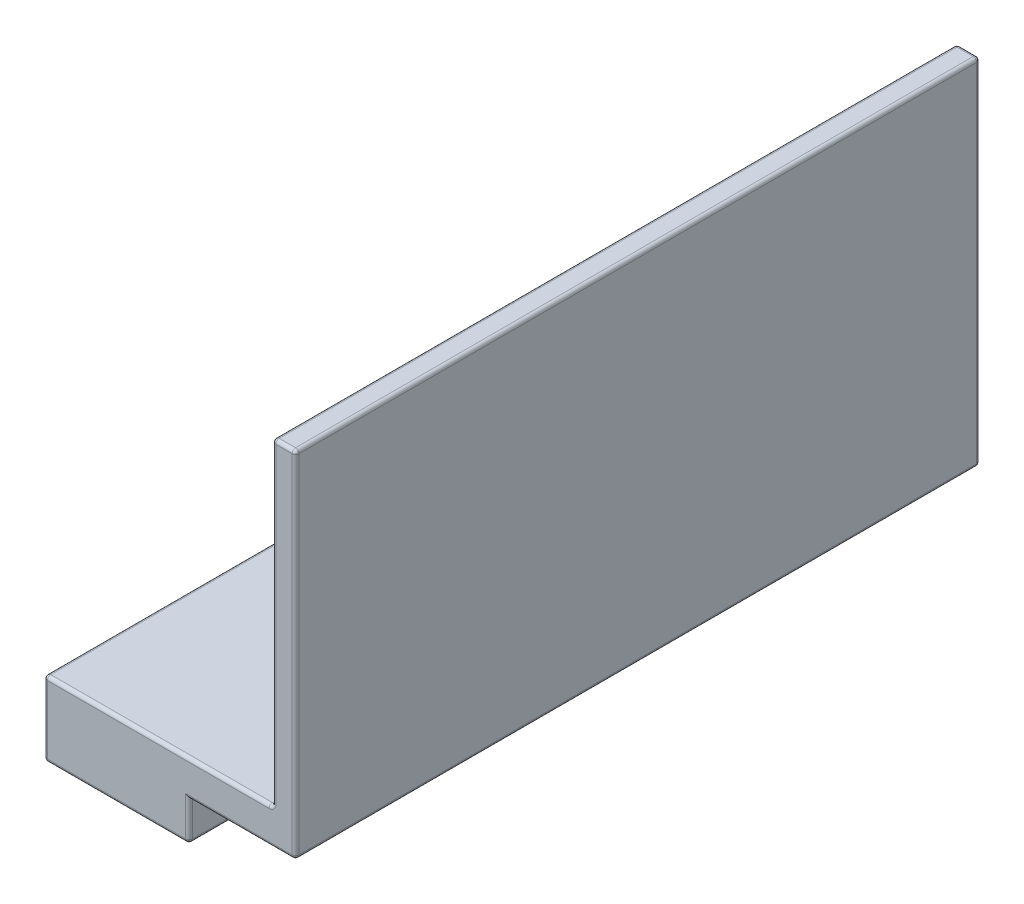
SolidWorks part; units mm, degrees
ref_plane "Front Plane" through (0, 0, 0) normal (0, 0, 1) x (1, 0, 0)
ref_plane "Top Plane" through (0, 0, 0) normal (0, 1, 0) x (1, 0, 0)
ref_plane "Right Plane" through (0, 0, 0) normal (1, 0, 0) x (0, 0, -1)
sketch "Sketch1" plane through (0, 0, 0) normal (0, 0, 1) x (1, 0, 0)
  line L1 (0, 0) -> (735, 0)
  line L2 (735, 0) -> (735, 1150.4)
  line L3 (735, 1150.4) -> (667.5, 1150.4)
  line L4 (667.5, 1150.4) -> (667.5, 218.8)
  line L5 (667.5, 218.8) -> (0, 218.8)
  line L8 (0, 218.8) -> (0, 0)
  dimension "D1" = 667.5
  dimension "D3" = 67.5
  dimension "D4" = 1150.4
  dimension "D5" = 218.8
extrude "Boss-Extrude1" add sketch "Sketch1" along normal blind 2000
sketch "Sketch3" plane through (0, 0, 0) normal (0, 0, -1) x (-1, 0, 0)
  line L1 (-735, 0) -> (-424, 0)
  line L2 (-735, 0) -> (-735, 115)
  line L3 (-735, 115) -> (-424, 115)
  line L4 (-424, 0) -> (-424, 115)
  dimension "D1" = 311
  dimension "D2" = 115
extrude "Cut-Extrude1" cut sketch "Sketch3" against normal up to next
sketch "Sketch2" plane through (0, 0, 0) normal (-1, 0, 0) x (0, 0, 1)
  line L0 (2000, 0) -> (0, 0) construction
  line L1 (20, 198.8) -> (1980, 198.8)
  line L2 (20, 198.8) -> (20, 20)
  line L3 (20, 20) -> (1980, 20)
  line L4 (1980, 198.8) -> (1980, 20)
  line L5 (20, 198.8) -> (1980, 20) construction
  line L6 (20, 20) -> (1980, 198.8) construction
  line L7 (0, 218.8) -> (0, 0) construction
  line L8 (2000, 218.8) -> (2000, 0) construction
  line L9 (2000, 218.8) -> (0, 218.8) construction
  point P0 (1000, 109.4)
  dimension "D1" = 20
  dimension "D2" = 20
  dimension "D3" = 20
  dimension "D4" = 20
extrude "Cut-Extrude2" cut sketch "Sketch2" against normal blind 310
fillet "Fillet2" radius 10 23 edges at (667.5, 684.6, 2000) (212, 0, 2000) (579.5, 115, 2000) (424, 57.5, 2000) (424, 0, 1000) (212, 0, 0) (424, 57.5, 0) (735, 115, 1000) (579.5, 115, 0) (735, 632.7, 0) (735, 632.7, 2000) (735, 1150.4, 1000) (701.25, 1150.4, 0) (701.25, 1150.4, 2000) (667.5, 1150.4, 1000) (333.75, 218.8, 2000) (667.5, 218.8, 1000) (667.5, 684.6, 0) (333.75, 218.8, 0) (0, 109.4, 2000) (0, 0, 1000) (0, 109.4, 0) (0, 218.8, 1000)
fillet "Fillet3" radius 2 8 edges at (0, 109.4, 1980) (0, 20, 1000) (0, 109.4, 20) (0, 198.8, 1000) (155, 198.8, 1980) (155, 198.8, 20) (155, 20, 20) (155, 20, 1980)
